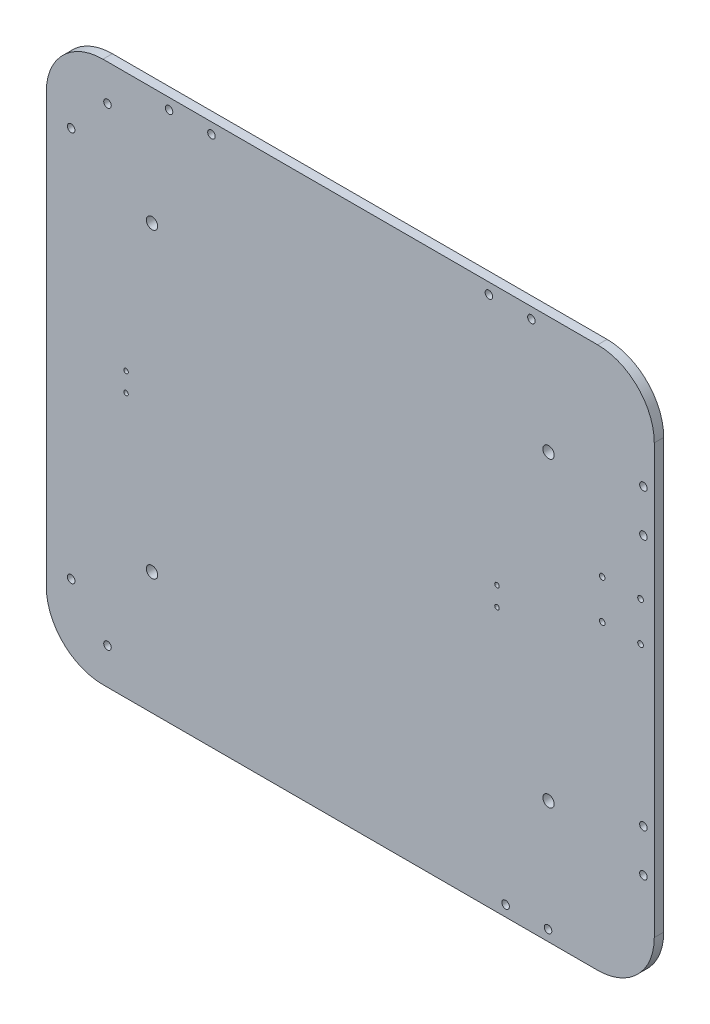
SolidWorks part; units mm, degrees
ref_plane "Front Plane" through (0, 0, 0) normal (0, 0, 1) x (1, 0, 0)
ref_plane "Top Plane" through (0, 0, 0) normal (0, 1, 0) x (1, 0, 0)
ref_plane "Right Plane" through (0, 0, 0) normal (1, 0, 0) x (0, 0, -1)
sketch "Sketch1" plane through (0, 0, 0) normal (0, 0, 1) x (1, 0, 0)
  line L0 (-26, -224.7) -> (236, -224.7)
  line L1 (105, 65) -> (105, 114.8128) construction
  line L2 (-60, -81.25) -> (105.0047, -81.25) construction
  line L30 (-60, 35) -> (-60, -20) construction
  line L31 (270, 35) -> (270, -20) construction
  line L48 (266, -194.7) -> (266, 32.2)
  line L49 (236, 62.2) -> (-26, 62.2)
  line L54 (-56, 32.2) -> (-56, -194.7)
  line L55 (-30, -227.5) -> (240, -227.5) construction
  line L56 (240, 65) -> (176.564, 65) construction
  arc A0 (-26, -224.7) -> (-56, -194.7) centre (-26, -194.7) cw
  arc A1 (236, -224.7) -> (266, -194.7) centre (236, -194.7) ccw
  arc A3 (266, 32.2) -> (236, 62.2) centre (236, 32.2) ccw
  arc A5 (-26, 62.2) -> (-56, 32.2) centre (-26, 32.2) ccw
  circle A7 centre (238.4253, -63.7) radius 1.5
  circle A9 centre (258.7253, -63.7) radius 1.5
  circle A11 centre (258.7253, -43) radius 1.5
  circle A13 centre (238.4253, -43) radius 1.5
  circle A18 centre (210, -160) radius 3
  circle A19 centre (-13.7646, -84.8) radius 1.2
  circle A20 centre (210, 0) radius 3
  circle A21 centre (-13.7646, -74.7) radius 1.2
  circle A22 centre (0, 0) radius 3
  circle A27 centre (182.7, -84.8) radius 1.2
  circle A29 centre (182.7, -74.7) radius 1.2
  circle A36 centre (0, -160) radius 3
  circle A48 centre (260.25, -146.4976) radius 2
  circle A49 centre (260.25, -168.9768) radius 2
  circle A50 centre (260.25, -13.1478) radius 2
  circle A51 centre (260.25, 9.3314) radius 2
  circle A52 centre (200.9167, 56.45) radius 2
  circle A53 centre (178.4375, 56.45) radius 2
  circle A54 centre (31.4877, 56.45) radius 2
  circle A55 centre (9.0084, 56.45) radius 2
  circle A56 centre (-23.5803, 43.0465) radius 2
  circle A57 centre (-42.8183, 22.1272) radius 2
  circle A58 centre (-42.8183, -184.6272) radius 2
  circle A59 centre (-23.5803, -205.5465) radius 2
  circle A60 centre (187.249, -218.95) radius 2
  circle A61 centre (209.7282, -218.95) radius 2
  dimension "D3" = 3
  dimension "D4" = 3
  dimension "D5" = 3
  dimension "D6" = 3
  dimension "D8" = 30
  dimension "D10" = 2.4
  dimension "D11" = 2.4
  dimension "D12" = 2.4
  dimension "D13" = 2.4
  dimension "D1" = 4
  dimension "D2" = 4
  dimension "D7" = 2.8
  dimension "D9" = 2.8
extrude "Boss-Extrude1" add sketch "Sketch1" along normal blind 5
